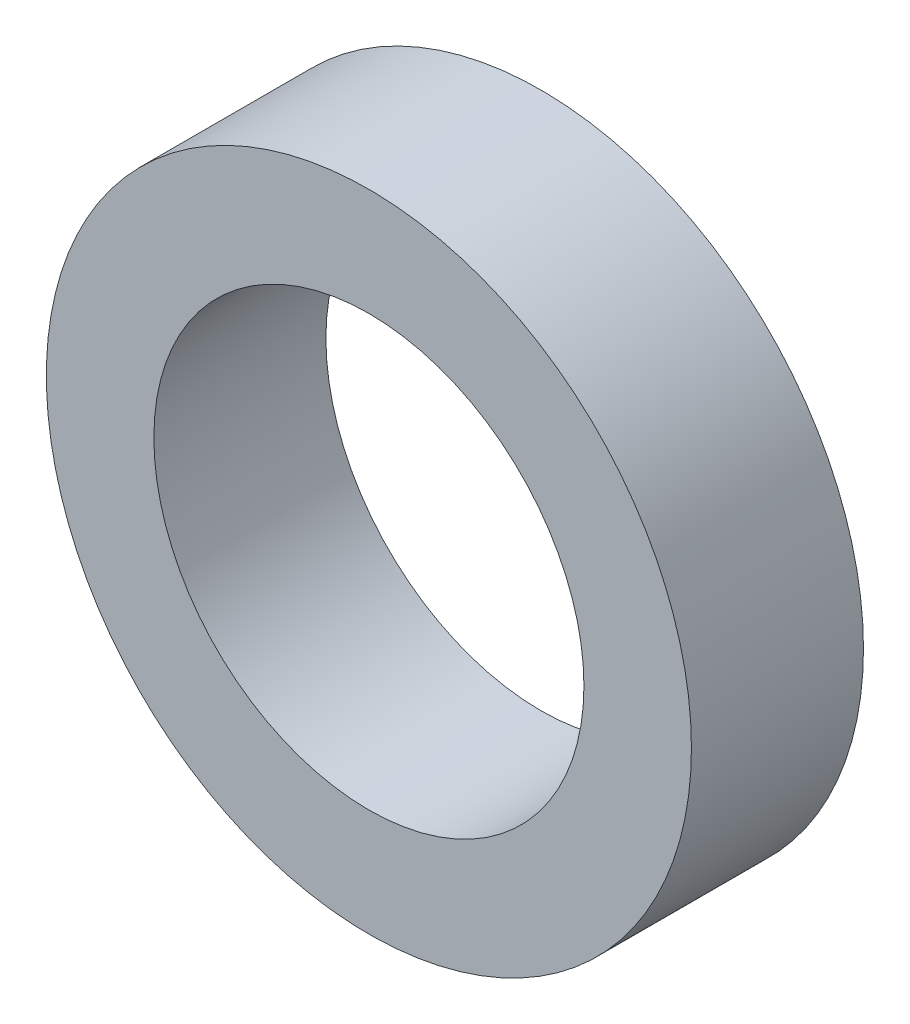
SolidWorks part; units mm, degrees
ref_plane "Front Plane" through (0, 0, 0) normal (0, 0, 1) x (1, 0, 0)
ref_plane "Top Plane" through (0, 0, 0) normal (0, 1, 0) x (1, 0, 0)
ref_plane "Right Plane" through (0, 0, 0) normal (1, 0, 0) x (0, 0, -1)
sketch "Sketch1" plane through (0, 0, 0) normal (0, 0, 1) x (1, 0, 0)
  circle A0 centre (0, 0) radius 5
  circle A1 centre (0, 0) radius 7.5
  dimension "D1" = 15
  dimension "D2" = 10
extrude "Boss-Extrude1" add sketch "Sketch1" along normal blind 4
